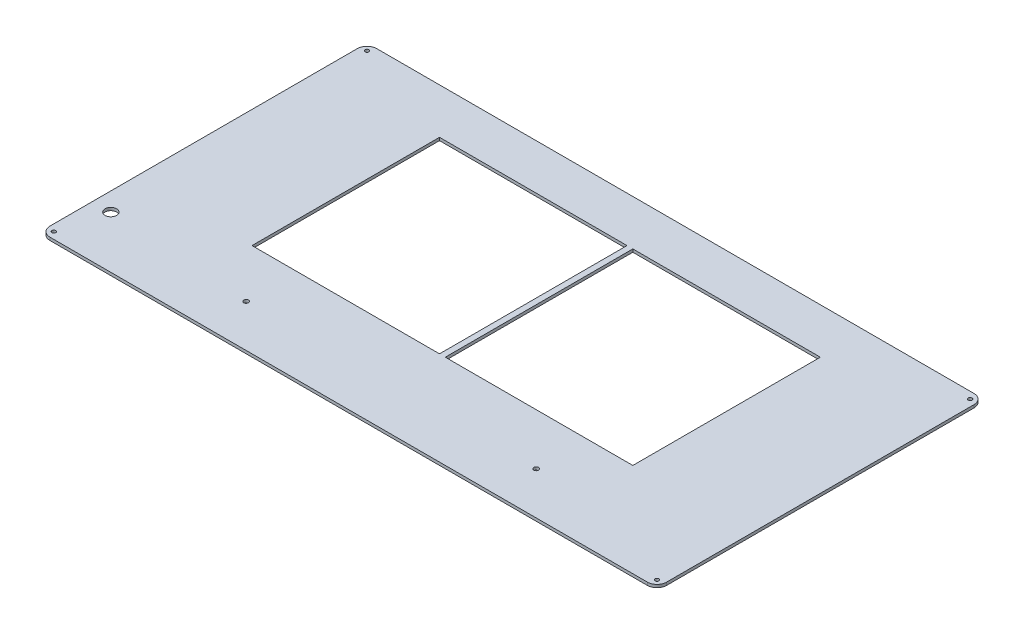
SolidWorks part; units mm, degrees
ref_plane "前视基准面" through (0, 0, 0) normal (0, 0, 1) x (1, 0, 0)
ref_plane "上视基准面" through (0, 0, 0) normal (0, 1, 0) x (1, 0, 0)
ref_plane "右视基准面" through (0, 0, 0) normal (1, 0, 0) x (0, 0, -1)
sketch "草图1" plane through (0, 0, 0) normal (0, 1, 0) x (1, 0, 0)
  line L0 (5, 350) -> (10, 350)
  line L5 (522, 103) -> (328, 103)
  line L6 (522, 103) -> (522, 297)
  line L7 (522, 297) -> (328, 297)
  line L8 (328, 103) -> (328, 297)
  line L9 (322, 103) -> (128, 103)
  line L10 (322, 103) -> (322, 297)
  line L11 (322, 297) -> (128, 297)
  line L12 (128, 103) -> (128, 297)
  line L13 (0, 345) -> (0, 340)
  line L14 (0, 340) -> (1, 340)
  line L15 (1, 342.5) -> (3, 342.5)
  line L16 (3, 342.5) -> (3, 330)
  line L17 (3, 330) -> (6, 330)
  line L18 (10, 350) -> (10, 349)
  line L19 (7.5, 349) -> (7.5, 347)
  line L20 (7.5, 347) -> (20, 347)
  line L21 (20, 347) -> (20, 344)
  line L22 (20, 344) -> (8.9, 344)
  line L23 (6, 330) -> (6, 341)
  line L24 (6, 341) -> (6.3448, 341)
  line L25 (8.9, 343.5) -> (8.9, 344)
  line L26 (1, 340) -> (1, 342.5)
  line L27 (10, 349) -> (7.5, 349)
  line L28 (328, 175) -> (322, 175)
  line L29 (325, 200) -> (325, 209.9738)
  line L30 (650, 345) -> (650, 340)
  line L31 (650, 340) -> (649, 340)
  line L32 (649, 340) -> (649, 342.5)
  line L33 (649, 342.5) -> (647, 342.5)
  line L34 (647, 342.5) -> (647, 330)
  line L35 (647, 330) -> (644, 330)
  line L36 (644, 330) -> (644, 341)
  line L37 (644, 341) -> (643.6552, 341)
  line L38 (641.1, 343.5) -> (641.1, 344)
  line L39 (630, 344) -> (641.1, 344)
  line L40 (630, 347) -> (630, 344)
  line L41 (642.5, 347) -> (630, 347)
  line L42 (642.5, 349) -> (642.5, 347)
  line L43 (640, 349) -> (642.5, 349)
  line L44 (640, 350) -> (640, 349)
  line L45 (645, 350) -> (640, 350)
  line L46 (0, 5) -> (0, 10)
  line L47 (0, 10) -> (1, 10)
  line L48 (1, 10) -> (1, 7.5)
  line L49 (1, 7.5) -> (3, 7.5)
  line L50 (3, 7.5) -> (3, 20)
  line L51 (3, 20) -> (6, 20)
  line L52 (6, 20) -> (6, 16)
  line L53 (6, 9) -> (6.3448, 9)
  line L54 (8.9, 6.5) -> (8.9, 6)
  line L55 (20, 6) -> (16, 6)
  line L56 (20, 3) -> (20, 6)
  line L57 (7.5, 3) -> (20, 3)
  line L58 (7.5, 1) -> (7.5, 3)
  line L59 (10, 1) -> (7.5, 1)
  line L60 (10, 0) -> (10, 1)
  line L61 (5, 0) -> (10, 0)
  line L62 (645, 0) -> (640, 0)
  line L63 (640, 0) -> (640, 1)
  line L64 (640, 1) -> (642.5, 1)
  line L65 (642.5, 1) -> (642.5, 3)
  line L66 (642.5, 3) -> (630, 3)
  line L67 (630, 3) -> (630, 6)
  line L68 (630, 6) -> (641.1, 6)
  line L69 (641.1, 6.5) -> (641.1, 6)
  line L70 (644, 9) -> (643.6552, 9)
  line L71 (644, 20) -> (644, 9)
  line L72 (647, 20) -> (644, 20)
  line L73 (647, 7.5) -> (647, 20)
  line L74 (649, 7.5) -> (647, 7.5)
  line L75 (649, 10) -> (649, 7.5)
  line L76 (650, 10) -> (649, 10)
  line L77 (650, 5) -> (650, 10)
  line L78 (644, 16) -> (644, 334)
  line L79 (634, 344) -> (16, 344)
  line L80 (6, 334) -> (6, 20)
  line L81 (20, 6) -> (634, 6)
  arc A0 (648, 350) -> (650, 348) centre (648, 348) cw
  arc A2 (2, 0) -> (0, 2) centre (2, 2) cw
  arc A3 (2, 350) -> (0, 348) centre (2, 348) ccw
  circle A4 centre (13, 13) radius 2
  circle A5 centre (637, 13) radius 2
  circle A6 centre (13, 337) radius 2
  circle A7 centre (637, 337) radius 2
  circle A8 centre (475, 50) radius 2.5
  circle A9 centre (175, 50) radius 2.5
  circle A10 centre (25, 60) radius 6
  arc A11 (5, 350) -> (0, 345) centre (5, 345) ccw
  arc A12 (8.1, 343.5) -> (6.5, 341.9) centre (6.5, 343.5) ccw
  arc A13 (8.1, 343.5) -> (8.9, 343.5) centre (8.5, 343.5) ccw
  arc A14 (6.3448, 341) -> (6.5, 341.9) centre (6.5, 341.4366) ccw
  arc A15 (645, 350) -> (650, 345) centre (645, 345) cw
  arc A16 (643.6552, 341) -> (643.5, 341.9) centre (643.5, 341.4366) cw
  arc A17 (641.9, 343.5) -> (643.5, 341.9) centre (643.5, 343.5) cw
  arc A18 (641.9, 343.5) -> (641.1, 343.5) centre (641.5, 343.5) cw
  arc A19 (5, 0) -> (0, 5) centre (5, 5) cw
  arc A20 (6.3448, 9) -> (6.5, 8.1) centre (6.5, 8.5634) cw
  arc A21 (8.1, 6.5) -> (6.5, 8.1) centre (6.5, 6.5) cw
  arc A22 (8.1, 6.5) -> (8.9, 6.5) centre (8.5, 6.5) cw
  arc A23 (641.9, 6.5) -> (641.1, 6.5) centre (641.5, 6.5) ccw
  arc A24 (641.9, 6.5) -> (643.5, 8.1) centre (643.5, 6.5) ccw
  arc A25 (643.6552, 9) -> (643.5, 8.1) centre (643.5, 8.5634) ccw
  arc A26 (645, 0) -> (650, 5) centre (645, 5) ccw
  arc A27 (6, 16) -> (16, 6) centre (16, 16) ccw
  arc A28 (644, 16) -> (634, 6) centre (634, 16) cw
  arc A29 (634, 344) -> (644, 334) centre (634, 334) cw
  arc A30 (16, 344) -> (6, 334) centre (16, 334) ccw
  point P9 (650, 0)
  point P12 (0, 0)
  point P15 (0, 350)
  dimension "D3" = 2
  dimension "D4" = 4
  dimension "D7" = 4
  dimension "D10" = 4
  dimension "D13" = 4
  dimension "D20" = 5
  dimension "D23" = 5
  dimension "D30" = 12
  dimension "D5" = 10
  dimension "D6" = 10
  dimension "D1" = 350
  dimension "D2" = 650
  dimension "D16" = 194
  dimension "D17" = 194
  dimension "D24" = 300
  dimension "D26" = 194
  dimension "D27" = 194
extrude "凸台-拉伸1" add sketch "草图1" against normal blind 3
